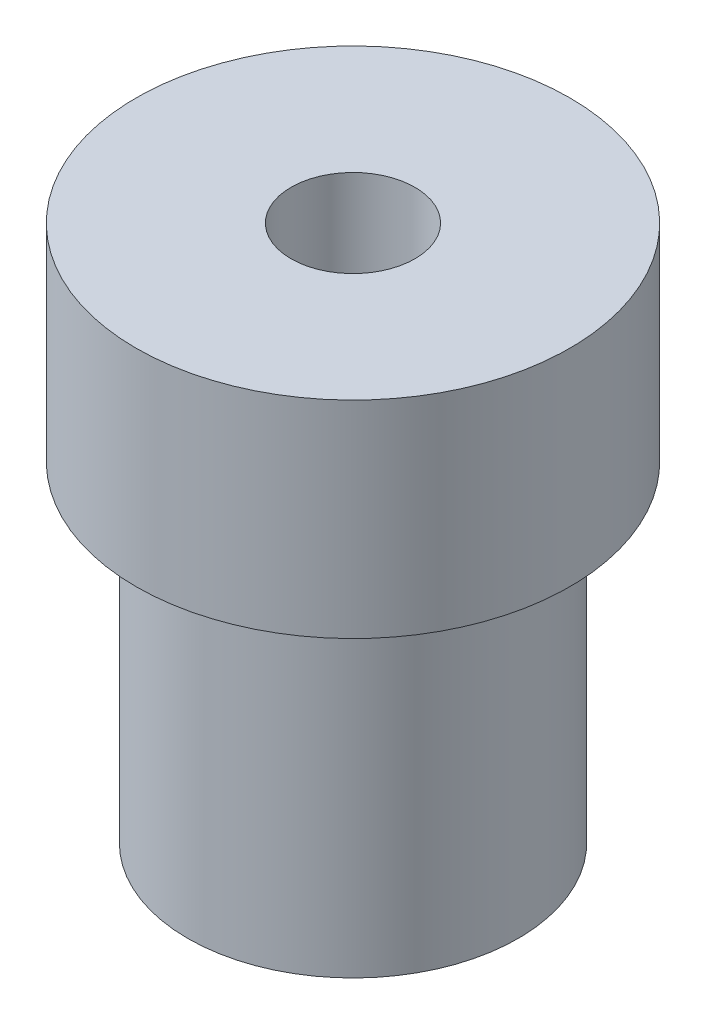
SolidWorks part; units mm, degrees
ref_plane "Front Plane" through (0, 0, 0) normal (0, 0, 1) x (1, 0, 0)
ref_plane "Top Plane" through (0, 0, 0) normal (0, 1, 0) x (1, 0, 0)
ref_plane "Right Plane" through (0, 0, 0) normal (1, 0, 0) x (0, 0, -1)
sketch "Sketch1" plane through (0, 0, 0) normal (0, 1, 0) x (1, 0, 0)
  circle A0 centre (0, 0) radius 10.5
extrude "Boss-Extrude1" add sketch "Sketch1" along normal blind 10
sketch "Sketch2" plane through (0, 0, 0) normal (0, 1, 0) x (1, 0, 0)
  circle A0 centre (0, 0) radius 8
extrude "Boss-Extrude2" add sketch "Sketch2" against normal blind 16
sketch "Sketch3" plane through (0, 0, 0) normal (0, 1, 0) x (1, 0, 0)
  circle A0 centre (0, 0) radius 3
extrude "Cut-Extrude1" cut sketch "Sketch3" against normal through all both and the other way through all
